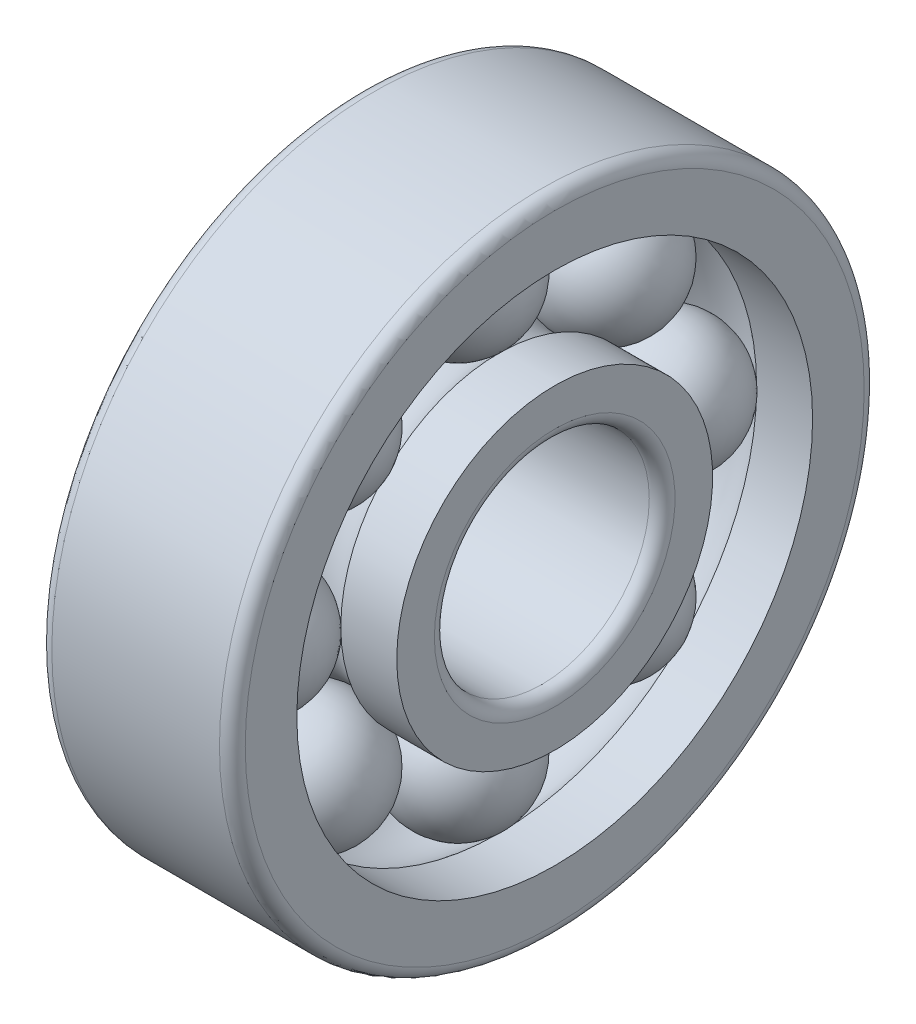
SolidWorks part; units mm, degrees
ref_plane "Alzado" through (0, 0, 0) normal (0, 0, 1) x (1, 0, 0)
ref_plane "Planta" through (0, 0, 0) normal (0, 1, 0) x (1, 0, 0)
ref_plane "Vista lateral" through (0, 0, 0) normal (1, 0, 0) x (0, 0, -1)
sketch "Sketch1" plane through (0, 0, 0) normal (0, 0, 1) x (1, 0, 0)
  line L0 (0, 0) -> (29.9021, 0) construction
  line L1 (0, 12) -> (2.6041, 12)
  line L2 (0, 15) -> (9, 15)
  line L3 (0, 15) -> (0, 12)
  line L4 (0, 5) -> (9, 5)
  line L5 (9, 15) -> (9, 12)
  line L6 (0, 7.35) -> (2.6041, 7.35)
  line L7 (0, 7.35) -> (0, 5)
  line L8 (9, 7.35) -> (9, 5)
  line L9 (0, 12) -> (0, 7.35) construction
  line L10 (0, 9.675) -> (9, 9.675) construction
  line L11 (6.3959, 7.35) -> (9, 7.35)
  line L12 (6.3959, 12) -> (9, 12)
  arc A0 (2.6041, 7.35) -> (6.3959, 7.35) centre (4.5, 9.675) ccw
  arc A1 (6.3959, 12) -> (2.6041, 12) centre (4.5, 9.675) ccw
  dimension "D6" = 6
  dimension "D1" = 9
  dimension "D2" = 5
  dimension "D3" = 15
  dimension "D4" = 12
  dimension "D5" = 7.35
revolve "Revolve1" add sketch "Sketch1" angle 360 about L0
fillet "Fillet1" radius 0.6 2 edges at (0, 0, 15) (9, 0, 15)
fillet "Fillet2" radius 0.6 2 edges at (0, 0, 5) (9, 0, 5)
sketch "Sketch2" plane through (0, 0, 0) normal (0, 0, 1) x (1, 0, 0)
  line L0 (4.5, 12.675) -> (4.5, 6.675)
  arc A0 (4.5, 12.675) -> (4.5, 6.675) centre (4.5, 9.675) ccw
  arc A1 (6.3959, 12) -> (2.6041, 12) centre (4.5, 9.675) ccw construction
revolve "Revolve2" add sketch "Sketch2" angle 360 about L0
pattern_circular "CirPattern2" count 8 over 360 about axis through (0, 0, 0) along (1, 0, 0) of bodies 103
sketch "Sketch3" plane through (0, 0, 0) normal (-1, 0, 0) x (0, 0, 1)
  arc A0 (-5.3394, 11.0807) -> (5.3394, 11.0807) centre (0, 0) cw construction
  circle A2 centre (0, 0) radius 12 construction
  text T0 "FAG 6200" font "Arial Narrow" height 1.5
  dimension "D1" = 0.3
extrude "Cut-Extrude1" cut sketch "Sketch3" against normal blind 0.3
